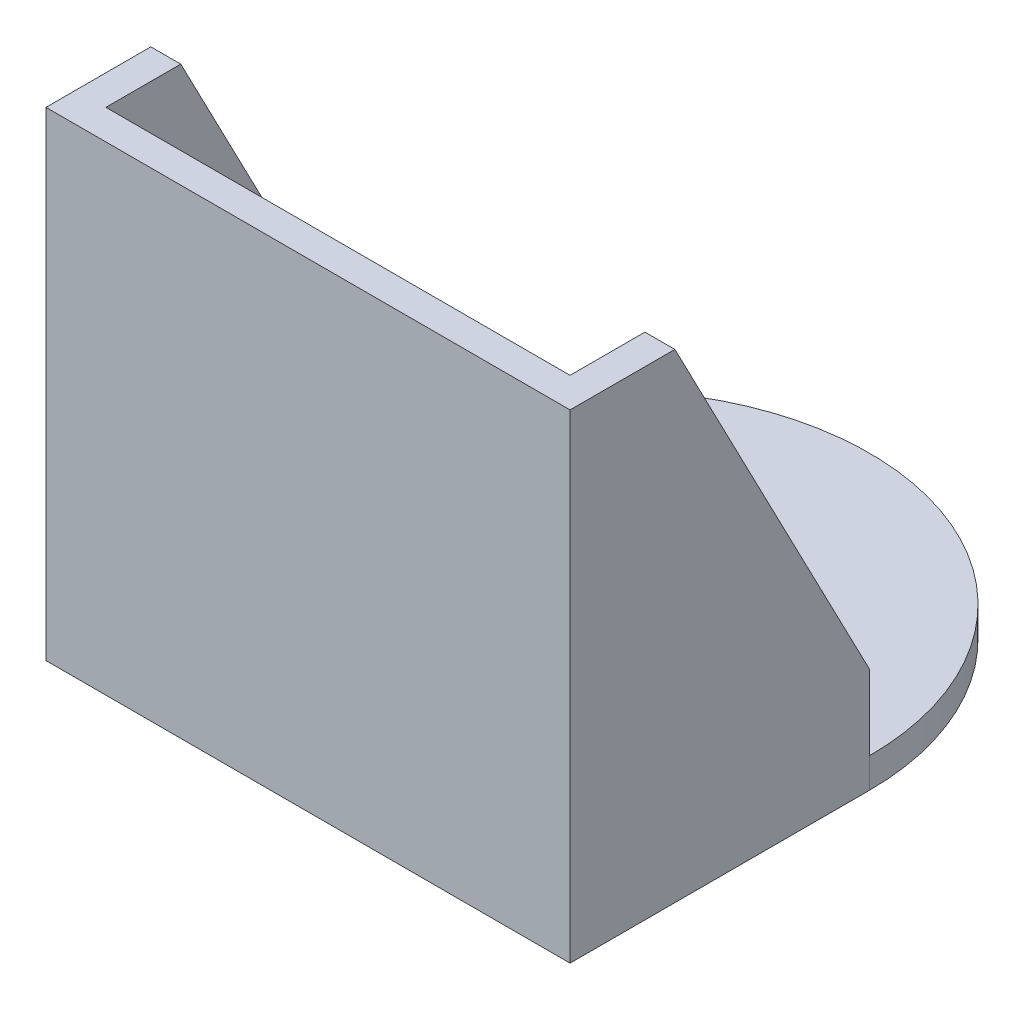
SolidWorks part; units mm, degrees
ref_plane "Front Plane" through (0, 0, 0) normal (0, 0, 1) x (1, 0, 0)
ref_plane "Top Plane" through (0, 0, 0) normal (0, 1, 0) x (1, 0, 0)
ref_plane "Right Plane" through (0, 0, 0) normal (1, 0, 0) x (0, 0, -1)
sketch "Sketch1" plane through (0, 0, 0) normal (0, 1, 0) x (1, 0, 0)
  line L0 (0, 0) -> (0, 25.4) construction
  line L1 (0, 0) -> (-21.997, -12.7) construction
  line L2 (0, 0) -> (21.997, -12.7) construction
  circle A0 centre (0, 0) radius 19.05
  circle A1 centre (0, 0) radius 44.45
  circle A2 centre (0, 0) radius 25.4 construction
  circle A3 centre (0, 25.4) radius 1.4106
  circle A4 centre (21.997, -12.7) radius 1.2219
  circle A5 centre (-21.997, -12.7) radius 0.9713
  dimension "D1" = 50.8
  dimension "D4" = 6.35
  dimension "D5" = 88.9
  dimension "D2" = 120
  dimension "D3" = 120
extrude "Boss-Extrude1" add sketch "Sketch1" along normal blind 5.08
sketch "Sketch2" plane through (0, 0, 0) normal (0, 1, 0) x (1, 0, 0)
  line L0 (-44.45, 0) -> (-44.45, -50.8)
  line L1 (-44.45, -50.8) -> (44.45, -50.8)
  line L2 (44.45, -50.8) -> (44.45, 0)
  circle A0 centre (0, 0) radius 44.45 construction
  arc A1 (-44.45, 0) -> (44.45, 0) centre (0, 0) ccw
  dimension "D1" = 50.8
extrude "Boss-Extrude2" add sketch "Sketch2" along normal up to surface (5.08 mm away) up to face at (21.997, 5.08, 13.9219)
sketch "Sketch3" plane through (0, 5.08, 0) normal (0, 1, 0) x (1, 0, 0)
  line L1 (-44.45, -50.8) -> (44.45, -50.8) construction
  line L4 (-44.45, -50.8) -> (44.45, -50.8)
extrude "Extrude-Thin1" add sketch "Sketch3" along normal blind 76.2 thin thin type one direction reverse wall 5.08
sketch "Sketch4" plane through (-44.45, 0, 0) normal (-1, 0, 0) x (0, 0, 1)
  line L0 (0, 5.08) -> (0, 17.78)
  line L1 (0, 17.78) -> (33.02, 81.28)
  line L2 (33.02, 81.28) -> (45.72, 81.28)
  line L3 (45.72, 81.28) -> (45.72, 5.08) construction
  line L4 (0, 5.08) -> (45.72, 5.08) construction
  line L5 (45.72, 81.28) -> (45.72, 5.08)
  line L6 (0, 5.08) -> (45.72, 5.08)
  dimension "D1" = 12.7
  dimension "D2" = 12.7
extrude "Boss-Extrude3" add sketch "Sketch4" against normal blind 5.08
mirror "Mirror1" about plane through (0, 0, 0) normal (1, 0, 0) of "Boss-Extrude3"
